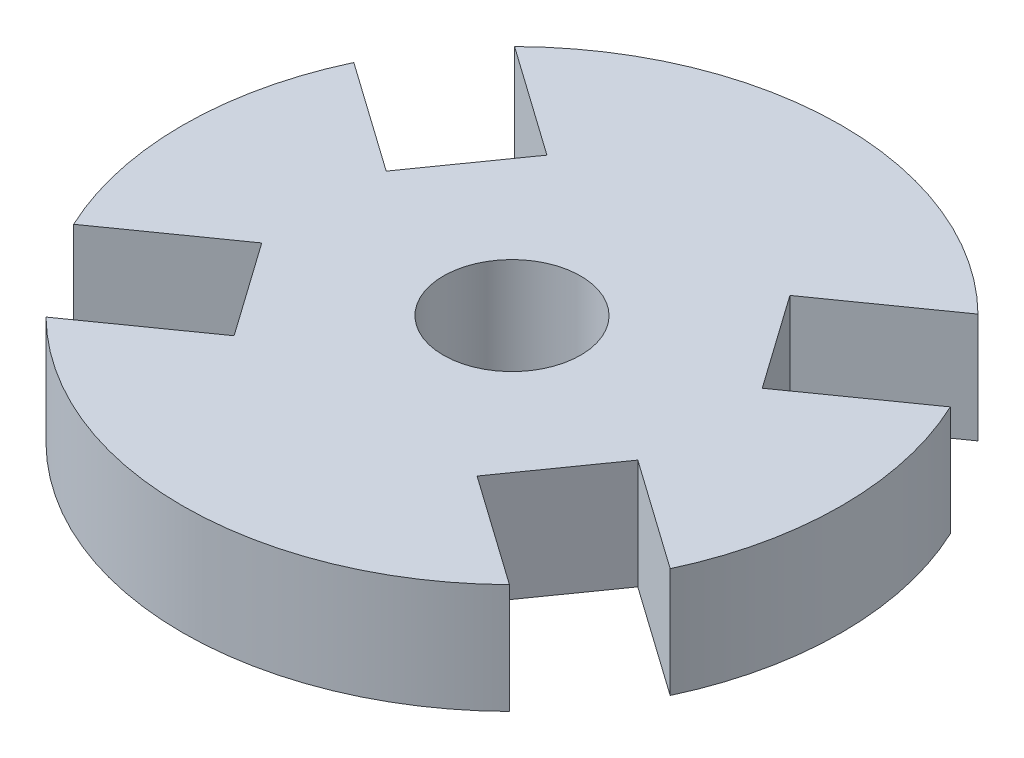
SolidWorks part; units mm, degrees
ref_plane "Alzado" through (0, 0, 0) normal (0, 0, 1) x (1, 0, 0)
ref_plane "Planta" through (0, 0, 0) normal (0, 1, 0) x (1, 0, 0)
ref_plane "Vista lateral" through (0, 0, 0) normal (1, 0, 0) x (0, 0, -1)
sketch "Croquis1" plane through (0, 0, 0) normal (0, 1, 0) x (1, 0, 0)
  circle A0 centre (0, 0) radius 12
  circle A1 centre (0, 0) radius 2.5
  dimension "D1" = 24
  dimension "D2" = 5
extrude "Saliente-Extruir1" add sketch "Croquis1" along normal blind 4
sketch "Croquis3" plane through (0, 4, 0) normal (0, 1, 0) x (1, 0, 0)
  line L0 (0, 0) -> (0, 12) construction
  line L1 (0, 0) -> (12, 0) construction
  line L2 (0, 0) -> (9.8013, 6.9235) construction
  line L8 (15.1784, 8.1508) -> (6.8473, 2.2658)
  line L9 (15.1784, 8.1508) -> (12.7552, 11.5812)
  line L10 (12.7552, 11.5812) -> (4.4241, 5.6962)
  line L11 (6.8473, 2.2658) -> (4.4241, 5.6962)
  line L12 (15.1784, 8.1508) -> (4.4241, 5.6962) construction
  line L13 (12.7552, 11.5812) -> (6.8473, 2.2658) construction
  line L15 (-15.1784, -8.1508) -> (-4.4241, -5.6962) construction
  line L16 (-12.7552, -11.5812) -> (-6.8473, -2.2658) construction
  line L17 (-4.4241, -5.6962) -> (-6.8473, -2.2658)
  line L18 (-15.1784, -8.1508) -> (-6.8473, -2.2658)
  line L19 (-12.7552, -11.5812) -> (-15.1784, -8.1508)
  line L20 (-12.7552, -11.5812) -> (-4.4241, -5.6962)
  line L21 (12.7552, -11.5812) -> (6.8473, -2.2658) construction
  line L22 (15.1784, -8.1508) -> (4.4241, -5.6962) construction
  line L23 (-12.7552, 11.5812) -> (-6.8473, 2.2658) construction
  line L24 (-15.1784, 8.1508) -> (-4.4241, 5.6962) construction
  line L25 (12.7552, -11.5812) -> (4.4241, -5.6962)
  line L26 (12.7552, -11.5812) -> (15.1784, -8.1508)
  line L27 (15.1784, -8.1508) -> (6.8473, -2.2658)
  line L28 (4.4241, -5.6962) -> (6.8473, -2.2658)
  line L29 (-6.8473, 2.2658) -> (-4.4241, 5.6962)
  line L30 (-12.7552, 11.5812) -> (-4.4241, 5.6962)
  line L31 (-15.1784, 8.1508) -> (-12.7552, 11.5812)
  line L32 (-15.1784, 8.1508) -> (-6.8473, 2.2658)
  circle A0 centre (0, 0) radius 12 construction
  dimension "D1" = 35.237
  dimension "D2" = 10.2
  dimension "D3" = 4.2
extrude "Cortar-Extruir1" cut sketch "Croquis3" against normal blind 4
equation "\"dface\"= 80"
equation "\"joind\"=10"
equation "\"P\"=.3"
equation "\"thickness\"=4"
equation "\"D1@Croquis1\" = \"P\" * \"dface\""
equation "\"D1@Saliente-Extruir1\"=\"thickness\""
equation "\"D2@Croquis3\"=\"joind\"+\"clear\""
equation "\"D3@Croquis3\"=\"thickness\"+\"clear\""
equation "\"clear\"=.2"
equation "\"D2@Croquis1\"=( \"P\" * \"dface\" ) - 4 * \"joind\""
equation "\"D1@Cortar-Extruir1\"=\"thickness\""
